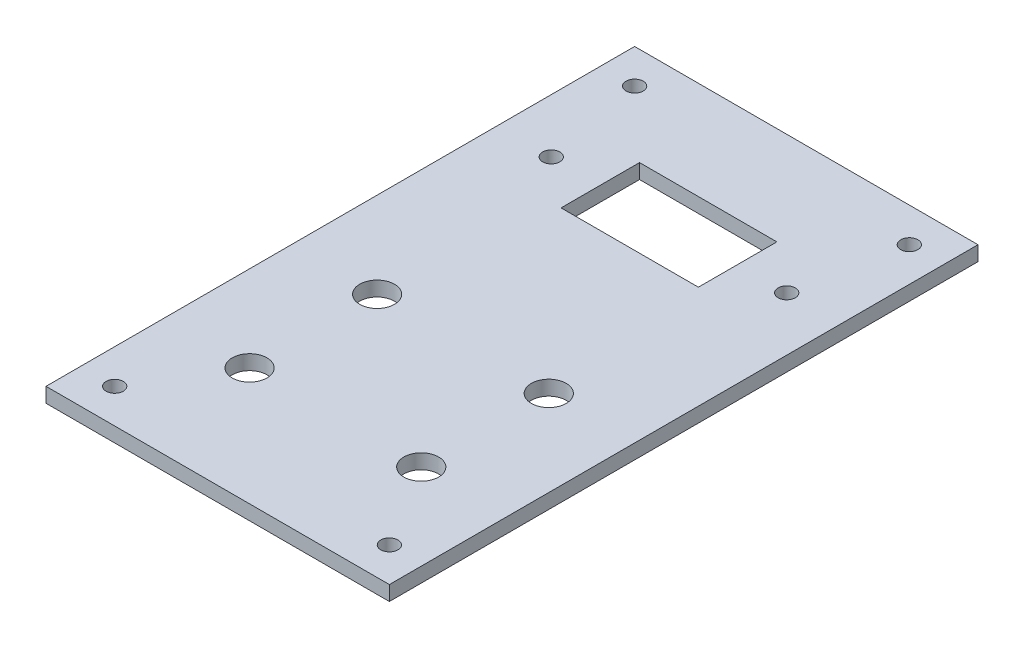
SolidWorks part; units mm, degrees
ref_plane "Front Plane" through (0, 0, 0) normal (0, 0, 1) x (1, 0, 0)
ref_plane "Top Plane" through (0, 0, 0) normal (0, 1, 0) x (1, 0, 0)
ref_plane "Right Plane" through (0, 0, 0) normal (1, 0, 0) x (0, 0, -1)
sketch "Sketch1" plane through (0, 0, 0) normal (0, 1, 0) x (1, 0, 0)
  line L1 (0, 0) -> (70, 0)
  line L2 (0, 0) -> (0, 120)
  line L3 (0, 120) -> (70, 120)
  line L4 (70, 0) -> (70, 120)
  dimension "D1" = 70
  dimension "D2" = 120
extrude "Boss-Extrude1" add sketch "Sketch1" along normal blind 3
sketch "Sketch2" plane through (0, 3, 0) normal (0, 1, 0) x (1, 0, 0)
  line L0 (0, 120) -> (0, 0) construction
  line L1 (21, 100) -> (49, 100)
  line L2 (21, 100) -> (21, 84)
  line L3 (21, 84) -> (49, 84)
  line L4 (49, 100) -> (49, 84)
  line L5 (70, 120) -> (0, 120) construction
  line L6 (0, 0) -> (70, 0) construction
  line L7 (70, 0) -> (70, 120) construction
  circle A0 centre (11, 92) radius 1.75
  circle A1 centre (59, 92) radius 1.75
  circle A2 centre (52.5, 24) radius 3.55
  circle A3 centre (17.5, 24) radius 3.55
  circle A4 centre (7, 113) radius 1.75
  circle A5 centre (63, 113) radius 1.75
  circle A6 centre (63, 7) radius 1.75
  circle A7 centre (7, 7) radius 1.75
  point P28 (31, 92)
  point P29 (31, 102)
  point P30 (11, 92)
  point P31 (11, 92)
  dimension "D5" = 3.5
  dimension "D6" = 3.5
  dimension "D11" = 7.1
  dimension "D12" = 7.1
  dimension "D13" = 3.5
  dimension "D14" = 3.5
  dimension "D15" = 3.5
  dimension "D16" = 3.5
  dimension "D1" = 28
  dimension "D2" = 16
  dimension "D3" = 10
  dimension "D4" = 10
  dimension "D7" = 21
  dimension "D9" = 60
  dimension "D10" = 60
  dimension "D17" = 7
  dimension "D18" = 7
  dimension "D19" = 7
  dimension "D20" = 7
  dimension "D21" = 7
  dimension "D22" = 7
  dimension "D23" = 7
  dimension "D24" = 7
  dimension "D25" = 35
  dimension "D26" = 17.5
extrude "Cut-Extrude1" cut sketch "Sketch2" against normal blind 3
sketch "Sketch4" plane through (0, 3, 0) normal (0, 1, 0) x (1, 0, 0)
  line L0 (0, 120) -> (0, 0) construction
  line L1 (70, 120) -> (0, 120) construction
  circle A0 centre (17.5, 50) radius 3.55
  circle A1 centre (52.5, 50) radius 3.55
  point P6 (0, 0)
  point P9 (57.5, 30)
  dimension "D1" = 7.1
  dimension "D2" = 7.1
  dimension "D3" = 35
  dimension "D4" = 17.5
  dimension "D5" = 70
extrude "Cut-Extrude2" cut sketch "Sketch4" against normal blind 12
